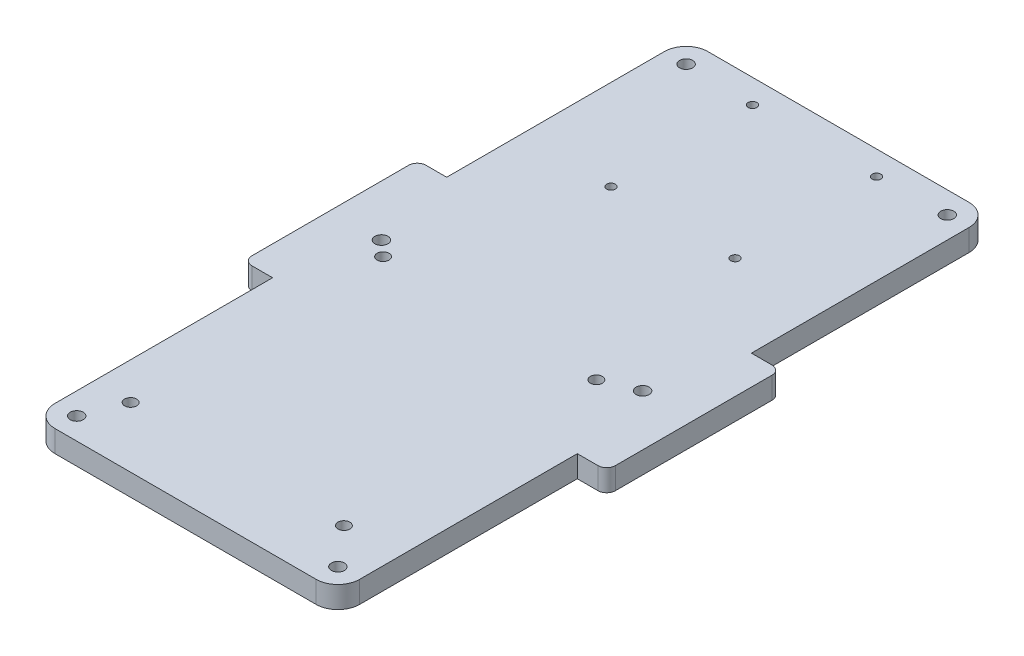
SolidWorks part; units mm, degrees
material "PMMA"
ref_plane "前视基准面" through (0, 0, 0) normal (0, 0, 1) x (1, 0, 0)
ref_plane "上视基准面" through (0, 0, 0) normal (0, 1, 0) x (1, 0, 0)
ref_plane "右视基准面" through (0, 0, 0) normal (1, 0, 0) x (0, 0, -1)
sketch "草图1" plane through (0, 0, 0) normal (0, 1, 0) x (1, 0, 0)
  line L0 (-30.9298, -28.8406) -> (39.0702, -28.8406) construction
  line L1 (-25.9298, 46.1594) -> (34.0702, 46.1594)
  line L2 (-30.9298, 41.1594) -> (-30.9298, -8.8406)
  line L3 (-25.9298, -103.8406) -> (34.0702, -103.8406)
  line L4 (39.0702, 41.1594) -> (39.0702, -8.8406)
  line L5 (-30.9298, 46.1594) -> (39.0702, -103.8406) construction
  line L6 (-30.9298, -103.8406) -> (39.0702, 46.1594) construction
  line L7 (4.0702, 46.1594) -> (4.0702, -103.8406) construction
  line L8 (-37.6798, -10.8406) -> (-37.6798, -46.8406)
  line L9 (-35.6798, -8.8406) -> (-30.9298, -8.8406)
  line L10 (-35.6798, -48.8406) -> (-30.9298, -48.8406)
  line L11 (43.8202, -48.8406) -> (39.0702, -48.8406)
  line L12 (45.8202, -10.8406) -> (45.8202, -46.8406)
  line L13 (43.8202, -8.8406) -> (39.0702, -8.8406)
  line L14 (-30.9298, -48.8406) -> (-30.9298, -98.8406)
  line L15 (39.0702, -48.8406) -> (39.0702, -98.8406)
  line L17 (20.8202, 5.6588) -> (-12.6798, 5.6588) construction
  line L18 (20.8202, 5.6588) -> (20.8202, 43.1588) construction
  line L19 (20.8202, 43.1588) -> (-12.6798, 43.1588) construction
  line L20 (-12.6798, 5.6588) -> (-12.6798, 43.1588) construction
  line L21 (20.8202, 5.6588) -> (-12.6798, 43.1588) construction
  line L22 (20.8202, 43.1588) -> (-12.6798, 5.6588) construction
  arc A0 (-30.9298, -98.8406) -> (-25.9298, -103.8406) centre (-25.9298, -98.8406) ccw
  arc A1 (34.0702, -103.8406) -> (39.0702, -98.8406) centre (34.0702, -98.8406) ccw
  arc A2 (39.0702, 41.1594) -> (34.0702, 46.1594) centre (34.0702, 41.1594) ccw
  arc A3 (-30.9298, 41.1594) -> (-25.9298, 46.1594) centre (-25.9298, 41.1594) cw
  arc A4 (45.8202, -46.8406) -> (43.8202, -48.8406) centre (43.8202, -46.8406) cw
  arc A5 (45.8202, -10.8406) -> (43.8202, -8.8406) centre (43.8202, -10.8406) ccw
  arc A6 (-35.6798, -48.8406) -> (-37.6798, -46.8406) centre (-35.6798, -46.8406) cw
  arc A7 (-37.6798, -10.8406) -> (-35.6798, -8.8406) centre (-35.6798, -10.8406) cw
  point P4 (4.0702, -28.8406)
  point P12 (-37.6798, -28.8406)
  point P32 (45.8202, -48.8406)
  point P35 (45.8202, -8.8406)
  point P38 (-37.6798, -48.8406)
  point P41 (-37.6798, -8.8406)
  point P42 (4.0702, 24.4088)
  dimension "D4" = 5
  dimension "D5" = 2
  dimension "D1" = 70
  dimension "D2" = 150
  dimension "D3" = 6.75
  dimension "D6" = 33.5
  dimension "D7" = 37.5
extrude "凸台-拉伸1" add sketch "草图1" along normal blind 5
sketch "草图3" plane through (0, 5, 0) normal (0, 1, 0) x (1, 0, 0)
  line L0 (4.0702, 43.1588) -> (4.0702, 5.6588) construction
  line L5 (20.8202, 5.6588) -> (-12.6798, 43.1588) construction
  line L6 (-12.6798, 5.6588) -> (20.8202, 5.6588) construction
  line L7 (-12.6798, 5.6588) -> (-12.6798, 43.1588) construction
  line L8 (-12.6798, 43.1588) -> (20.8202, 43.1588) construction
  line L9 (26.5702, -89.9626) -> (-22.4298, -89.9626) construction
  line L10 (26.5702, -89.9626) -> (26.5702, -31.9626) construction
  line L11 (26.5702, -31.9626) -> (-22.4298, -31.9626) construction
  line L12 (-22.4298, -89.9626) -> (-22.4298, -31.9626) construction
  line L13 (26.5702, -89.9626) -> (-22.4298, -31.9626) construction
  line L14 (26.5702, -31.9626) -> (-22.4298, -89.9626) construction
  line L15 (20.8202, 5.6588) -> (20.8202, 43.1588) construction
  line L16 (-12.6798, 5.6588) -> (20.8202, 43.1588) construction
  line L17 (-12.6798, 43.1588) -> (20.8202, 5.6588) construction
  line L18 (-12.6798, 40.6588) -> (-10.1798, 40.6588) construction
  line L19 (-10.1798, 40.6588) -> (-10.1798, 43.1588) construction
  line L20 (20.8202, 43.1588) -> (-12.6798, 43.1588) construction
  line L21 (-12.6798, 24.4088) -> (20.8202, 24.4088) construction
  circle A0 centre (34.0702, 41.1594) radius 1.5
  circle A1 centre (-25.9298, 41.1594) radius 1.5
  circle A2 centre (-25.9298, -98.8406) radius 1.5
  circle A3 centre (34.0702, -98.8406) radius 1.5
  circle A4 centre (34.0702, -28.8406) radius 1.5
  circle A5 centre (-25.9298, -28.8406) radius 1.5
  circle A10 centre (26.5702, -31.9626) radius 1.375
  circle A11 centre (-22.4298, -31.9626) radius 1.375
  circle A12 centre (26.5702, -89.9626) radius 1.375
  circle A13 centre (-22.4298, -89.9626) radius 1.375
  circle A14 centre (-10.1798, 40.6588) radius 1
  circle A15 centre (18.3202, 40.6588) radius 1
  circle A16 centre (-10.1798, 8.1588) radius 1
  circle A17 centre (18.3202, 8.1588) radius 1
  point P16 (4.0702, 24.4088)
  point P17 (4.0702, 24.4088)
  point P35 (2.0702, -60.9626)
  dimension "D1" = 49
  dimension "D2" = 58
extrude "切除-拉伸1" cut sketch "草图3" against normal through all
